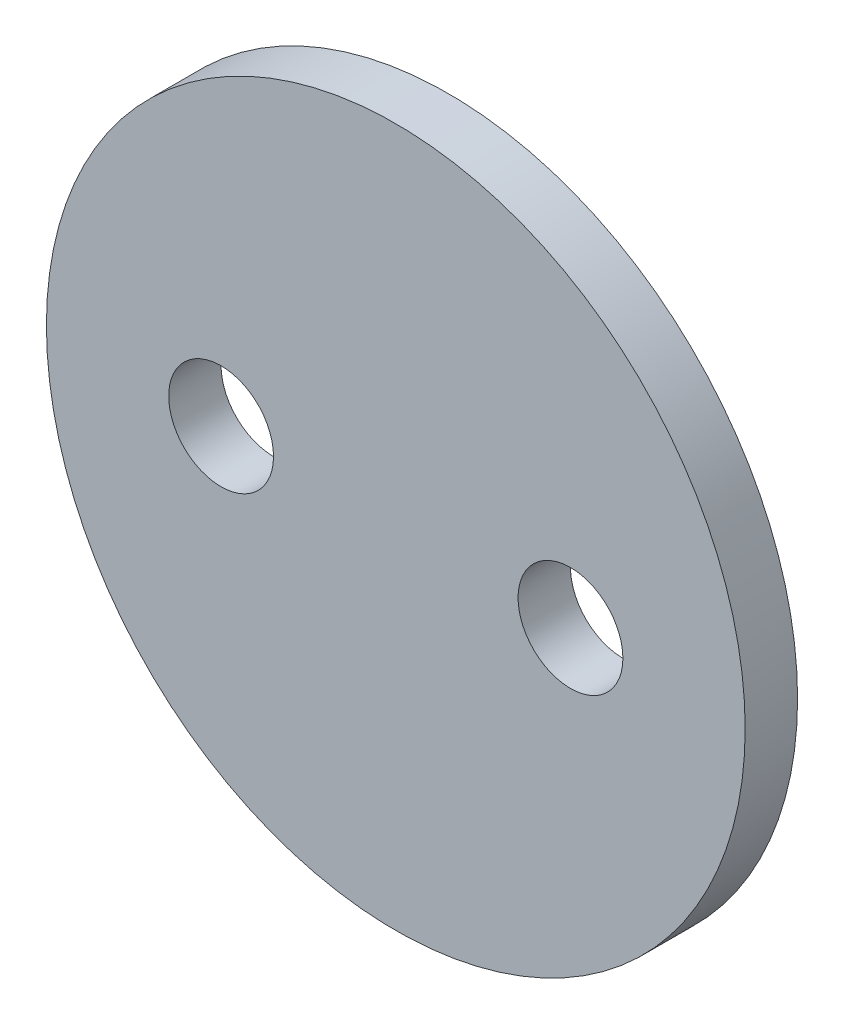
SolidWorks part; units mm, degrees
ref_plane "Спереди" through (0, 0, 0) normal (0, 0, 1) x (1, 0, 0)
ref_plane "Сверху" through (0, 0, 0) normal (0, 1, 0) x (1, 0, 0)
ref_plane "Справа" through (0, 0, 0) normal (1, 0, 0) x (0, 0, -1)
sketch "Эскиз1" plane through (0, 0, 0) normal (0, 0, 1) x (1, 0, 0)
  line L0 (0, 0) -> (-5, 0) construction
  line L1 (0, 0) -> (5, 0) construction
  circle A0 centre (0, 0) radius 10
  circle A1 centre (-5, 0) radius 1.5
  circle A2 centre (5, 0) radius 1.5
  dimension "D1" = 5
  dimension "D2" = 3
  dimension "D3" = 20
extrude "Бобышка-Вытянуть1" add sketch "Эскиз1" along normal blind 1.5
